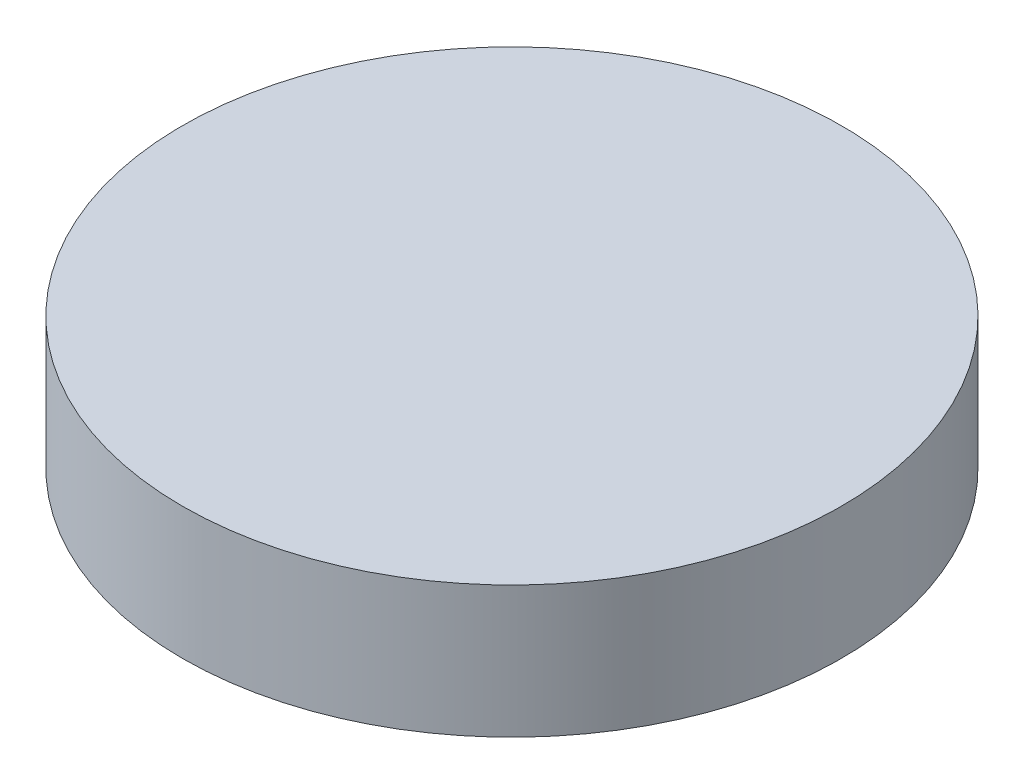
SolidWorks part; units mm, degrees
material "Copper"
ref_plane "Front Plane" through (0, 0, 0) normal (0, 0, 1) x (1, 0, 0)
ref_plane "Top Plane" through (0, 0, 0) normal (0, 1, 0) x (1, 0, 0)
ref_plane "Right Plane" through (0, 0, 0) normal (1, 0, 0) x (0, 0, -1)
sketch "Sketch2" plane through (0, 0, 0) normal (0, 1, 0) x (1, 0, 0)
  circle A0 centre (0, 0) radius 50
  dimension "D1" = 100
extrude "Boss-Extrude1" add sketch "Sketch2" along normal blind 20
